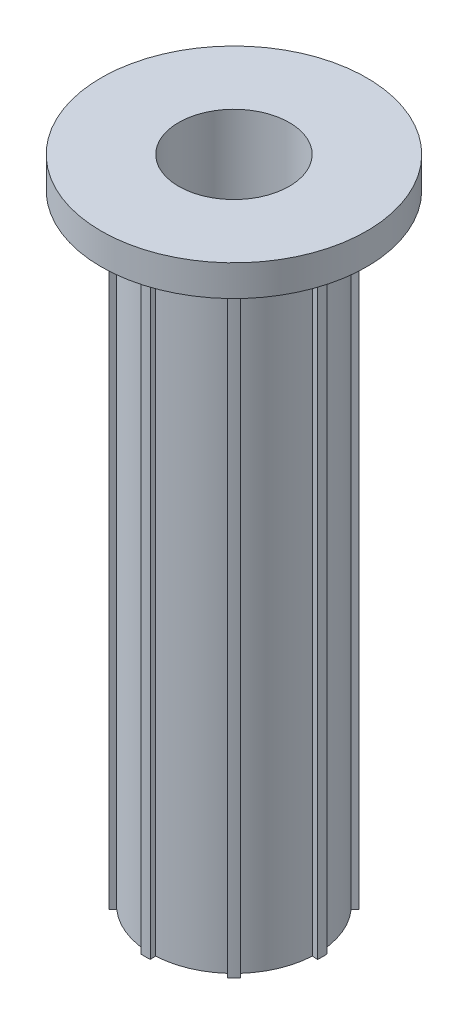
SolidWorks part; units mm, degrees
material "PET"
ref_plane "Front Plane" through (0, 0, 0) normal (0, 0, 1) x (1, 0, 0)
ref_plane "Top Plane" through (0, 0, 0) normal (0, 1, 0) x (1, 0, 0)
ref_plane "Right Plane" through (0, 0, 0) normal (1, 0, 0) x (0, 0, -1)
sketch "Sketch2" plane through (0, 0, 0) normal (0, 1, 0) x (1, 0, 0)
  circle A0 centre (0, 0) radius 5.08
  dimension "D1" = 10.16
extrude "Boss-Extrude1" add sketch "Sketch2" along normal blind 35.56
sketch "Sketch3" plane through (0, 0, 0) normal (0, -1, 0) x (1, 0, 0)
  line L1 (-7.0848, -6.3664) -> (-7.5344, -6.816)
  line L2 (-10.1473, -0.508) -> (-9.5114, -0.508)
  line L3 (-0.508, 10.1473) -> (-0.508, 9.5114)
  line L4 (-10.1473, 0.508) -> (-9.5114, 0.508)
  line L5 (0.508, 10.1473) -> (0.508, 9.5114)
  line L6 (-7.5344, 6.816) -> (-7.0848, 6.3664)
  line L7 (-6.3664, -7.0848) -> (-6.816, -7.5344)
  line L8 (-0.508, -9.5114) -> (-0.508, -10.1473)
  line L9 (6.816, 7.5344) -> (6.3664, 7.0848)
  line L10 (-6.816, 7.5344) -> (-6.3664, 7.0848)
  line L11 (7.5344, 6.816) -> (7.0848, 6.3664)
  line L12 (0.508, -9.5114) -> (0.508, -10.1473)
  line L13 (6.3664, -7.0848) -> (6.816, -7.5344)
  line L14 (7.0848, -6.3664) -> (7.5344, -6.816)
  line L15 (9.5114, -0.508) -> (10.1473, -0.508)
  line L16 (9.5114, 0.508) -> (10.1473, 0.508)
  arc A0 (-9.5114, -0.508) -> (-7.0848, -6.3664) centre (0, 0) ccw
  arc A1 (-7.0848, 6.3664) -> (-9.5114, 0.508) centre (0, 0) ccw
  arc A2 (-10.1473, -0.508) -> (-7.5344, -6.816) centre (0, 0) ccw
  arc A3 (-7.5344, 6.816) -> (-10.1473, 0.508) centre (0, 0) ccw
  arc A4 (-0.508, 9.5114) -> (-6.3664, 7.0848) centre (0, 0) ccw
  arc A5 (-0.508, 10.1473) -> (-6.816, 7.5344) centre (0, 0) ccw
  arc A6 (6.3664, 7.0848) -> (0.508, 9.5114) centre (0, 0) ccw
  arc A7 (6.816, 7.5344) -> (0.508, 10.1473) centre (0, 0) ccw
  arc A8 (9.5114, 0.508) -> (7.0848, 6.3664) centre (0, 0) ccw
  arc A9 (10.1473, 0.508) -> (7.5344, 6.816) centre (0, 0) ccw
  arc A10 (7.0848, -6.3664) -> (9.5114, -0.508) centre (0, 0) ccw
  arc A11 (7.5344, -6.816) -> (10.1473, -0.508) centre (0, 0) ccw
  arc A12 (0.508, -9.5114) -> (6.3664, -7.0848) centre (0, 0) ccw
  arc A13 (0.508, -10.1473) -> (6.816, -7.5344) centre (0, 0) ccw
  arc A14 (-6.3664, -7.0848) -> (-0.508, -9.5114) centre (0, 0) ccw
  arc A15 (-6.816, -7.5344) -> (-0.508, -10.1473) centre (0, 0) ccw
sketch "Sketch4" plane through (0, 35.56, 0) normal (0, 1, 0) x (1, 0, 0)
  circle A0 centre (0, 0) radius 7.62
  dimension "D1" = 15.24
extrude "Boss-Extrude2" add sketch "Sketch4" along normal blind 1.778
sketch "Sketch5" plane through (0, 37.338, 0) normal (0, 1, 0) x (1, 0, 0)
  circle A0 centre (0, 0) radius 3.175
  dimension "D1" = 6.35
extrude "Cut-Extrude2" cut sketch "Sketch5" against normal through all
sketch "Sketch6" plane through (0, 0, 0) normal (0, -1, 0) x (1, 0, 0)
  line L0 (-3.7786, 3.3954) -> (-3.5424, 3.1832)
  line L1 (-0.2709, 5.0728) -> (-0.254, 4.7557)
  line L2 (-3.3954, 3.7786) -> (-3.1832, 3.5424)
  line L3 (0.2709, 5.0728) -> (0.254, 4.7557)
  line L4 (3.3954, 3.7786) -> (3.1832, 3.5424)
  line L5 (3.7786, 3.3954) -> (3.5424, 3.1832)
  line L6 (5.0728, 0.2709) -> (4.7557, 0.254)
  line L7 (5.0728, -0.2709) -> (4.7557, -0.254)
  line L8 (3.1832, -3.5424) -> (3.3954, -3.7786)
  line L9 (3.5424, -3.1832) -> (3.7786, -3.3954)
  line L10 (-4.7557, 0.254) -> (-5.0728, 0.2709)
  line L11 (-4.7557, -0.254) -> (-5.0728, -0.2709)
  line L12 (-3.5424, -3.1832) -> (-3.7786, -3.3954)
  line L13 (-3.1832, -3.5424) -> (-3.3954, -3.7786)
  line L14 (-0.254, -4.7557) -> (-0.2709, -5.0728)
  line L15 (0.254, -4.7557) -> (0.2709, -5.0728)
  arc A0 (-3.5424, 3.1832) -> (-4.7557, 0.254) centre (0, 0) ccw
  arc A1 (-3.7786, 3.3954) -> (-5.0728, 0.2709) centre (0, 0) ccw
  arc A2 (-0.2709, 5.0728) -> (-3.3954, 3.7786) centre (0, 0) ccw
  arc A3 (-0.254, 4.7557) -> (-3.1832, 3.5424) centre (0, 0) ccw
  arc A4 (0.2709, -5.0728) -> (3.3954, -3.7786) centre (0, 0) ccw
  arc A5 (0.254, -4.7557) -> (3.1832, -3.5424) centre (0, 0) ccw
  arc A6 (-3.3954, -3.7786) -> (-0.2709, -5.0728) centre (0, 0) ccw
  arc A7 (-3.1832, -3.5424) -> (-0.254, -4.7557) centre (0, 0) ccw
  arc A8 (-5.0728, -0.2709) -> (-3.7786, -3.3954) centre (0, 0) ccw
  arc A9 (-4.7557, -0.254) -> (-3.5424, -3.1832) centre (0, 0) ccw
  arc A10 (3.7786, -3.3954) -> (5.0728, -0.2709) centre (0, 0) ccw
  arc A11 (3.5424, -3.1832) -> (4.7557, -0.254) centre (0, 0) ccw
  arc A12 (5.0728, 0.2709) -> (3.7786, 3.3954) centre (0, 0) ccw
  arc A13 (4.7557, 0.254) -> (3.5424, 3.1832) centre (0, 0) ccw
  arc A14 (3.3954, 3.7786) -> (0.2709, 5.0728) centre (0, 0) ccw
  arc A15 (3.1832, 3.5424) -> (0.254, 4.7557) centre (0, 0) ccw
  dimension "D1" = 9.525
extrude "Cut-Extrude3" cut sketch "Sketch6" against normal blind 35.56
